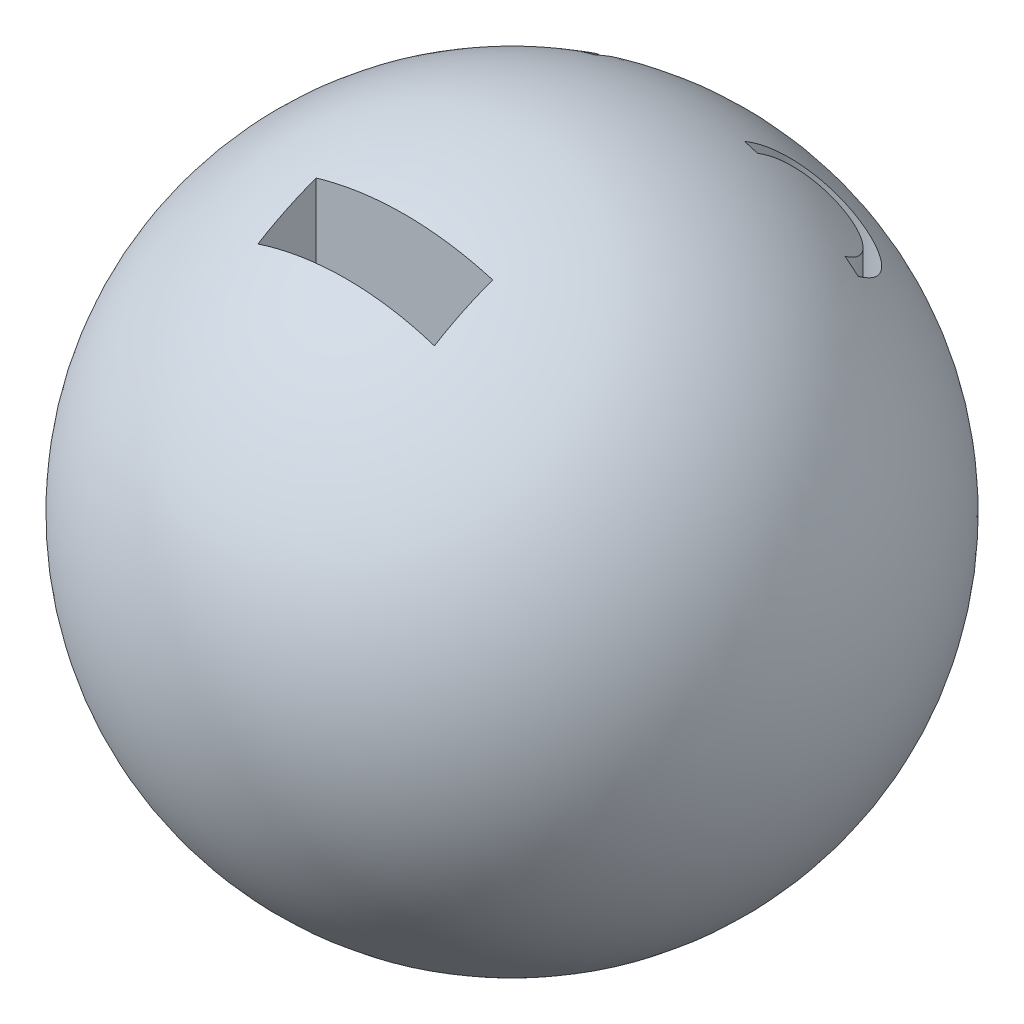
SolidWorks part; units mm, degrees
ref_plane "前视基准面" through (0, 0, 0) normal (0, 0, 1) x (1, 0, 0)
ref_plane "上视基准面" through (0, 0, 0) normal (0, 1, 0) x (1, 0, 0)
ref_plane "右视基准面" through (0, 0, 0) normal (1, 0, 0) x (0, 0, -1)
other "Configuration Table"
sketch "草图4" plane through (0, 0, 0) normal (1, 0, 0) x (0, 0, -1)
  line L0 (0, 0) -> (0, 17.552)
  line L1 (0, -25) -> (0, 25)
  arc A0 (0, 25) -> (0, -25) centre (0, 0) ccw
ref_axis "基准轴1" through (0, 0, 0) along (0, 1, 0)
revolve "旋转1" add sketch "草图4" angle 360 about axis through (0, 0, 0) along (0, 1, 0)
ref_plane "基准面1" through (0, 10, 0) normal (0, 1, 0) x (1, 0, 0)
sketch "草图5" plane through (0, 10, 0) normal (0, 1, 0) x (1, 0, 0)
  circle A0 centre (0, 0) radius 10
sketch "草图6" plane through (0, 10, 0) normal (0, 1, 0) x (1, 0, 0)
  line L0 (-14.3089, 11.9407) -> (-13.3089, 11.9407)
  line L1 (-5.6911, 11.9407) -> (-6.6911, 11.9407)
  line L2 (0, 0) -> (0, 13.2069)
  line L3 (14.3089, 11.9407) -> (13.3089, 11.9407)
  line L4 (5.6911, 11.9407) -> (6.6911, 11.9407)
  line L5 (-6.6911, -8.1552) -> (6.6911, -8.1552)
  line L6 (-6.6911, -8.1552) -> (-6.6911, -12.5736)
  line L7 (-6.6911, -12.5736) -> (6.6911, -12.5736)
  line L8 (6.6911, -8.1552) -> (6.6911, -12.5736)
  arc A0 (-5.6911, 11.9407) -> (-14.3089, 11.9407) centre (-10, 11.9407) ccw
  arc A1 (-13.3089, 11.9407) -> (-6.6911, 11.9407) centre (-10, 11.9407) cw
  arc A2 (5.6911, 11.9407) -> (14.3089, 11.9407) centre (10, 11.9407) cw
  arc A3 (13.3089, 11.9407) -> (6.6911, 11.9407) centre (10, 11.9407) ccw
extrude "切除-拉伸1" cut sketch "草图6" along normal through all contours L0 A1 L1 A0 | L8 L5 L6 L7 | A2 L3 A3 L4
